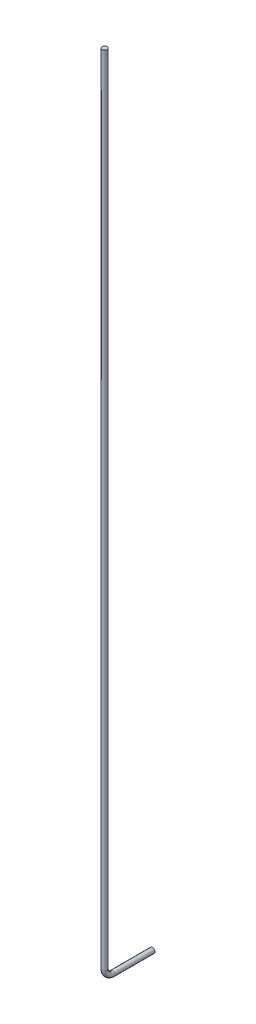
SolidWorks part; units mm, degrees
ref_plane "正面" through (0, 0, 0) normal (0, 0, 1) x (1, 0, 0)
ref_plane "平面" through (0, 0, 0) normal (0, 1, 0) x (1, 0, 0)
ref_plane "右側面" through (0, 0, 0) normal (1, 0, 0) x (0, 0, -1)
sketch "ｽｹｯﾁ1" plane through (0, 0, 0) normal (0, 0, 1) x (1, 0, 0)
  circle A0 centre (0, 0) radius 1.6
  dimension "D1" = 3.2
extrude "ﾎﾞｽ - 押し出し1" add sketch "ｽｹｯﾁ1" along normal blind 20
sketch "ｽｹｯﾁ2" plane through (0, 0, 20) normal (0, 0, 1) x (1, 0, 0)
  circle A1 centre (0, 0) radius 1.6
  circle A2 centre (0, 0) radius 1.6
  dimension "D1" = 0
sketch "ｽｹｯﾁ3" plane through (0, 0, 0) normal (1, 0, 0) x (0, 0, -1)
  line L0 (-20, 0) -> (-25, 0)
  line L1 (-20, 1.6) -> (-20, -1.6) construction
  line L2 (-30, 5) -> (-30, 505)
  line L3 (-20, 1.6) -> (-20, -1.6) construction
  arc A0 (-25, 0) -> (-30, 5) centre (-25, 5) cw
  point P8 (-30, 0)
  dimension "D2" = 5
  dimension "D1" = 10
  dimension "D3" = 500
sweep "ｽｲｰﾌﾟ1" add profiles "ｽｹｯﾁ2" path "ｽｹｯﾁ3"
